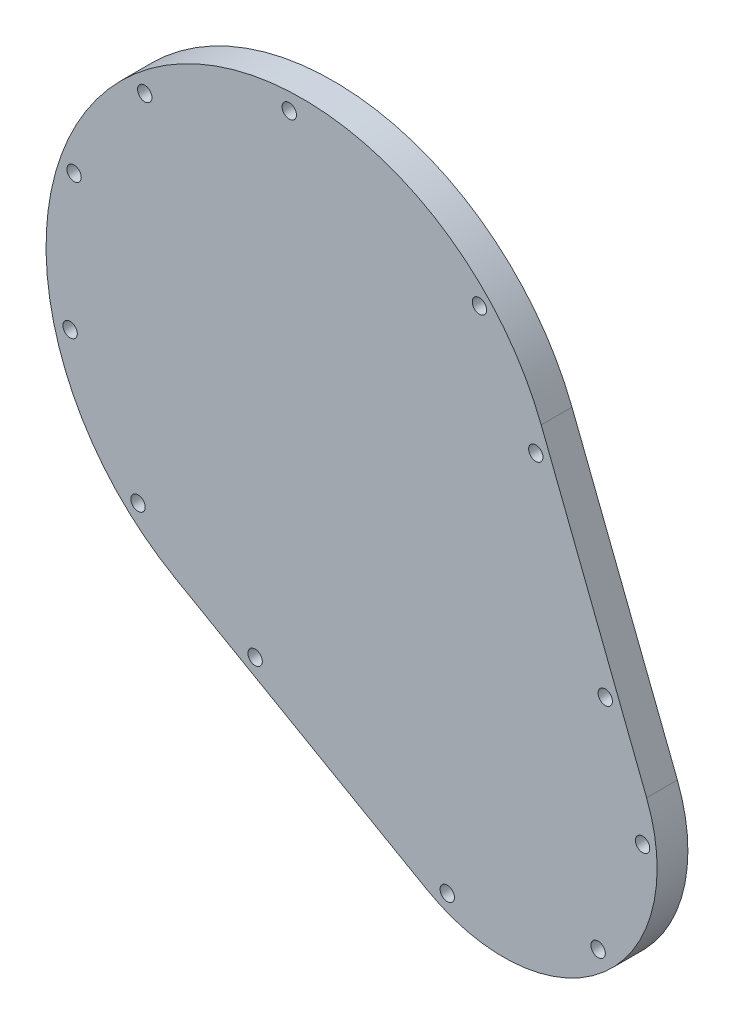
SolidWorks part; units mm, degrees
ref_plane "Front Plane" through (0, 0, 0) normal (0, 0, 1) x (1, 0, 0)
ref_plane "Top Plane" through (0, 0, 0) normal (0, 1, 0) x (1, 0, 0)
ref_plane "Right Plane" through (0, 0, 0) normal (1, 0, 0) x (0, 0, -1)
sketch "Sketch1" plane through (0, 0, 0) normal (0, 0, 1) x (1, 0, 0)
  line L0 (0, 0) -> (31.1871, -17.8237)
  line L1 (58.3872, 5.6385) -> (45.3334, 39.1037)
  arc A0 (31.1871, -17.8237) -> (58.3872, 5.6385) centre (40.6396, -1.2843) ccw
  arc A1 (45.3334, 39.1037) -> (0, 0) centre (15.7541, 27.5658) ccw
  dimension "D1" = 19.05
  dimension "D2" = 31.75
  dimension "D3" = 88.9
extrude "Boss-Extrude1" add sketch "Sketch1" along normal blind 3.81
hole_wizard "#50 (0.07) Diameter Hole3" positions "Sketch13" profile "Sketch14" hole size "#50" standard "ANSI Inch" end condition through all
sketch "Sketch13" plane through (0, 0, 3.81) normal (0, 0, 1) x (1, 0, 0)
  point P0 (-3.7702, 50.0984)
  point P2 (14.1273, 57.1787)
  point P4 (37.6792, 48.0333)
  point P8 (57.8876, 0.3886)
  point P10 (52.3807, -13.6245)
  point P12 (33.6965, -16.968)
  point P14 (9.8988, -3.5449)
  point P16 (-4.606, 5.7481)
  point P18 (-13.0139, 20.1545)
  point P20 (-12.5222, 37.167)
  point P28 (44.6612, 35.7411)
  point P30 (53.2657, 13.8609)
sketch "Sketch14" plane through (-3.7702, 50.0984, 3.81) normal (1, 0, 0) x (0, -1, 0)
  line L0 (0, 0) -> (0, 3.81)
  line L1 (0, 3.81) -> (0.889, 3.81)
  line L2 (0.889, 3.81) -> (0.889, 0)
  line L5 (0.889, 0) -> (0, 0)
  line L11 (0, -6.35) -> (0, 107.95) construction
  dimension "Thru Hole Dia." = 1.778
  dimension "Thru Hole Depth" = 3.81
